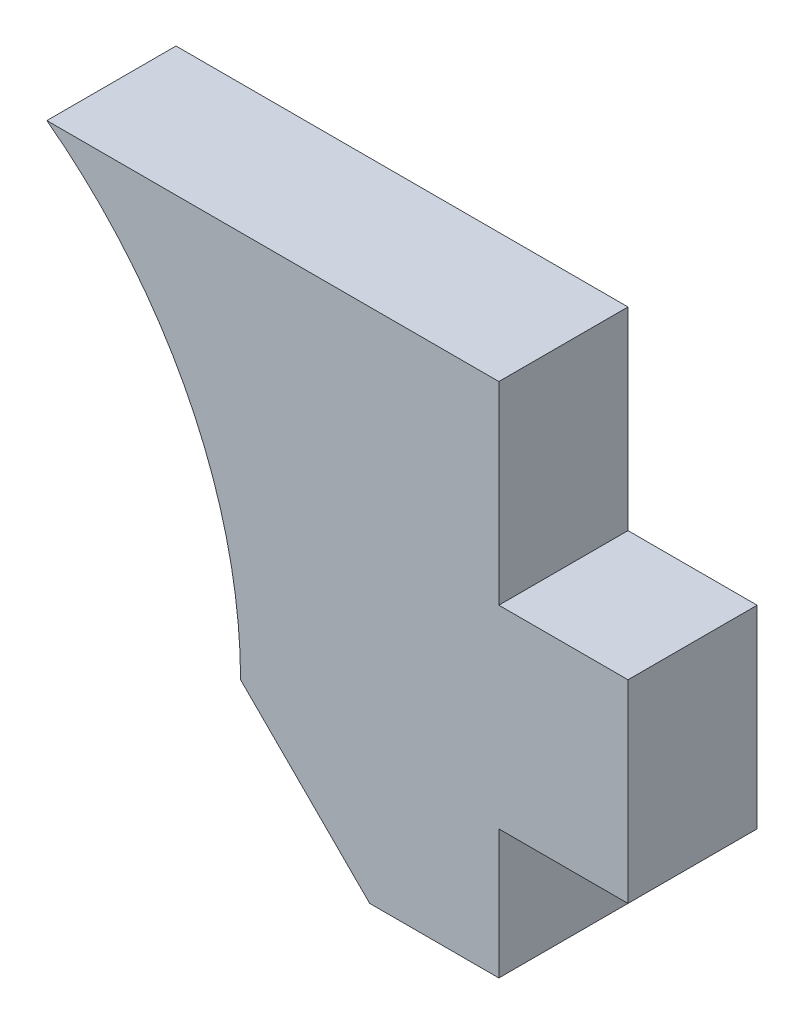
SolidWorks part; units mm, degrees
ref_plane "Front Plane" through (0, 0, 0) normal (0, 0, 1) x (1, 0, 0)
ref_plane "Top Plane" through (0, 0, 0) normal (0, 1, 0) x (1, 0, 0)
ref_plane "Right Plane" through (0, 0, 0) normal (1, 0, 0) x (0, 0, -1)
sketch "Sketch1" plane through (0, 0, 0) normal (0, 0, 1) x (1, 0, 0)
  line L664 (490.9249, 8.7496) -> (490.9249, 5.7496)
  line L665 (490.9249, 5.7496) -> (487.9249, 5.7496)
  line L666 (487.9249, 5.7496) -> (484.9249, 8.7496)
  line L667 (480.4249, 17.7496) -> (490.9249, 17.7496)
  line L668 (490.9249, 17.7496) -> (490.9249, 13.2496)
  line L669 (490.9249, 13.2496) -> (493.9249, 13.2496)
  line L670 (493.9249, 13.2496) -> (493.9249, 8.7496)
  line L671 (493.9249, 8.7496) -> (490.9249, 8.7496)
  arc A0 (484.9249, 8.7496) -> (480.4249, 17.7496) centre (473.6749, 8.7496) ccw
extrude "Boss-Extrude1" add sketch "Sketch1" along normal blind 3
